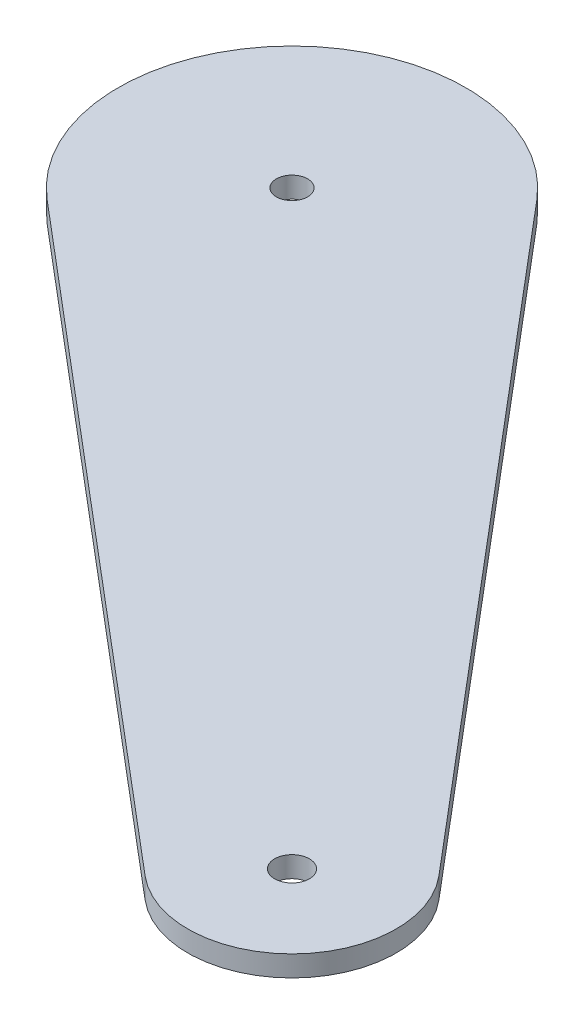
SolidWorks part; units mm, degrees
ref_plane "前视基准面" through (0, 0, 0) normal (0, 0, 1) x (1, 0, 0)
ref_plane "上视基准面" through (0, 0, 0) normal (0, 1, 0) x (1, 0, 0)
ref_plane "右视基准面" through (0, 0, 0) normal (1, 0, 0) x (0, 0, -1)
other "Configuration Table"
sketch "草图2" plane through (0, 0, 0) normal (0, 1, 0) x (1, 0, 0)
  line L0 (-140.5033, 0) -> (6884.6605, 0) construction
  line L1 (0, -140.5033) -> (0, 6884.6605) construction
  line L2 (0, 0) -> (42.4264, -42.4264)
  line L3 (42.4264, -42.4264) -> (-42.4264, 42.4264)
  line L4 (-58.5694, 23.3371) -> (32.7406, -53.88)
  line L5 (-23.3371, 58.5694) -> (53.88, -32.7406)
  circle A0 centre (-42.4264, 42.4264) radius 25
  circle A1 centre (42.4264, -42.4264) radius 15
  dimension "D3" = 50
  dimension "D4" = 30
  dimension "D1" = 60
  dimension "D2" = 120
extrude "凸台-拉伸2" add sketch "草图2" along normal blind 3
sketch "草图4" plane through (0, 3, 0) normal (0, 1, 0) x (1, 0, 0)
  line L0 (-58.5694, 23.3371) -> (32.7406, -53.88)
  line L1 (-58.5694, 23.3371) -> (32.7406, -53.88) construction
  line L2 (-23.3371, 58.5694) -> (53.88, -32.7406)
  line L3 (-23.3371, 58.5694) -> (53.88, -32.7406) construction
  line L4 (-56.6323, 25.6278) -> (34.6777, -51.5893)
  line L5 (-25.6278, 56.6323) -> (51.5893, -34.6777)
  circle A0 centre (-42.4264, 42.4264) radius 25
  circle A1 centre (42.4264, -42.4264) radius 15
  circle A2 centre (-42.4264, 42.4264) radius 22
  circle A3 centre (42.4264, -42.4264) radius 12
  circle A4 centre (-42.4264, 42.4264) radius 2.25
  circle A5 centre (42.4264, -42.4264) radius 2.5
  point P26 (0, 0)
  dimension "D3" = 4.5
  dimension "D4" = 5
  dimension "D1" = 3
  dimension "D2" = 3
extrude "切除-拉伸2" cut sketch "草图4" against normal through all contours A4 | A5
